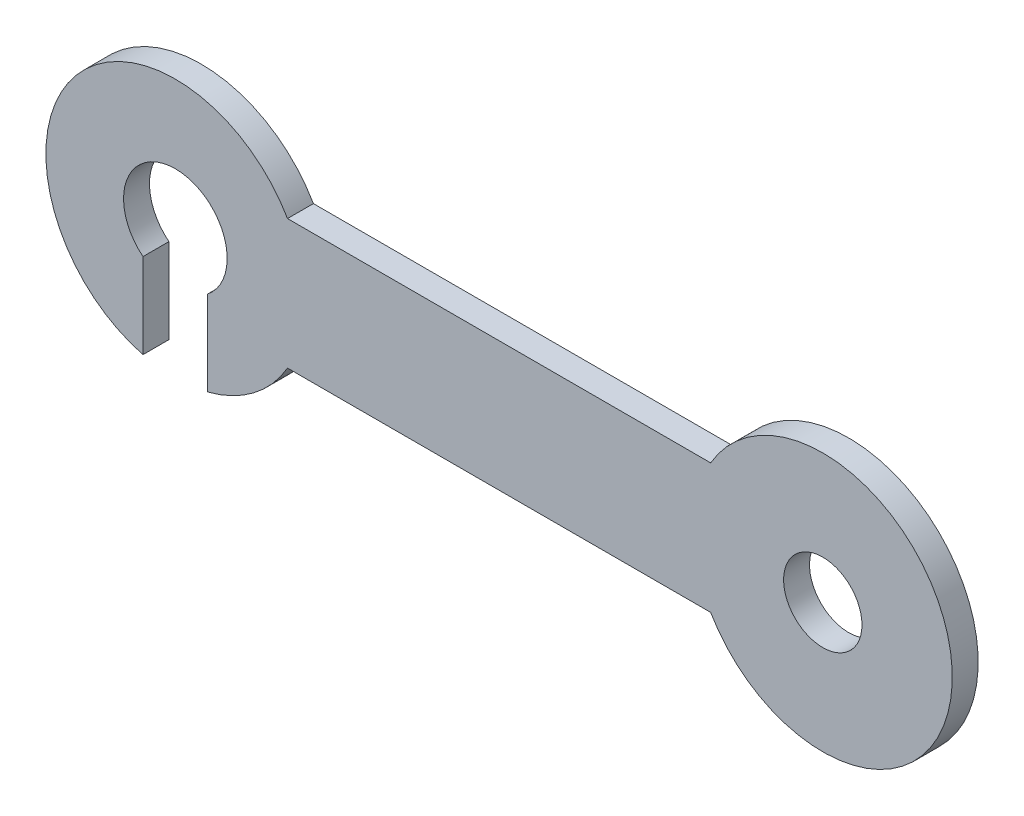
SolidWorks part; units mm, degrees
ref_plane "Front Plane" through (0, 0, 0) normal (0, 0, 1) x (1, 0, 0)
ref_plane "Top Plane" through (0, 0, 0) normal (0, 1, 0) x (1, 0, 0)
ref_plane "Right Plane" through (0, 0, 0) normal (1, 0, 0) x (0, 0, -1)
sketch "Sketch1" plane through (0, 0, 0) normal (0, 0, 1) x (1, 0, 0)
  circle A0 centre (0, 0) radius 20
  dimension "D1" = 40
extrude "Boss-Extrude1" add sketch "Sketch1" along normal blind 4
sketch "Sketch3" plane through (0, 0, 0) normal (0, 0, 1) x (1, 0, 0)
  line L0 (0, 10) -> (0, 0)
  line L1 (0, 0) -> (0, -10)
  line L2 (0, -10) -> (100, -10)
  line L3 (100, -10) -> (100, 0)
  line L4 (100, 0) -> (100, 10)
  line L5 (100, 10) -> (0, 10)
  circle A0 centre (100, 0) radius 20
  dimension "D6" = 40
  dimension "D1" = 10
  dimension "D2" = 10
  dimension "D3" = 10
  dimension "D4" = 10
  dimension "D5" = 100
extrude "Boss-Extrude2" add sketch "Sketch3" along normal blind 4 contours L2 A0 L5 L4 L3 | L5 A0 L2 L3 L4 | A0 L5 L0 L1 L2
sketch "Sketch4" plane through (0, 0, 0) normal (0, 0, 1) x (1, 0, 0)
  circle A0 centre (0, 0) radius 8
  dimension "D1" = 16
extrude "Cut-Extrude1" cut sketch "Sketch4" along normal blind 4
sketch "Sketch5" plane through (0, 0, 0) normal (0, 0, 1) x (1, 0, 0)
  line L1 (-5, -23.9724) -> (5, -23.9724)
  line L2 (-5, -23.9724) -> (-5, -4.8396)
  line L3 (-5, -4.8396) -> (5, -4.8396)
  line L4 (5, -23.9724) -> (5, -4.8396)
  line L5 (-5, -23.9724) -> (5, -4.8396) construction
  line L6 (-5, -4.8396) -> (5, -23.9724) construction
  point P0 (0, -14.406)
  point P5 (0, 0)
  dimension "D1" = 10
  dimension "D2" = 0
extrude "Cut-Extrude3" cut sketch "Sketch5" along normal blind 4
sketch "Sketch6" plane through (0, 0, 0) normal (0, 0, 1) x (1, 0, 0)
  circle A0 centre (100, 0) radius 6.05
  dimension "D1" = 12.1
extrude "Cut-Extrude4" cut sketch "Sketch6" along normal blind 4
